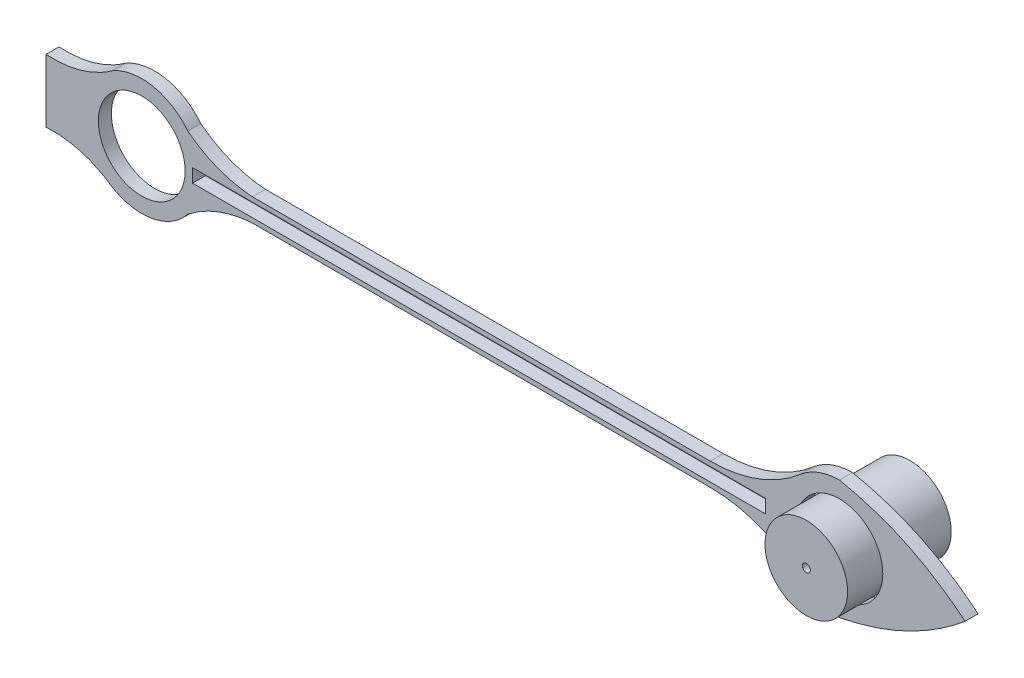
SolidWorks part; units mm, degrees
ref_plane "Plan de face" through (0, 0, 0) normal (0, 0, 1) x (1, 0, 0)
ref_plane "Plan de dessus" through (0, 0, 0) normal (0, 1, 0) x (1, 0, 0)
ref_plane "Plan de droite" through (0, 0, 0) normal (1, 0, 0) x (0, 0, -1)
sketch "Esquisse1" plane through (0, 0, 0) normal (0, 0, 1) x (1, 0, 0)
  line L0 (10.3412, -0.1574) -> (1.5013, -0.1574) construction
  line L1 (10.2021, 0) -> (10.2021, 10.4852) construction
  line L2 (2.2237, 0) -> (9.9473, 0) construction
  line L3 (2.2237, 0) -> (8.5558, 0)
  line L4 (0.6927, -0.1574) -> (1.2927, -0.1574) construction
  line L7 (8.5558, -0.3149) -> (2.2237, -0.3149)
  line L9 (1.2927, -0.1574) -> (-0.6312, -0.1574) construction
  line L10 (1.5013, -0.1574) -> (2.3649, -0.1574) construction
  line L11 (-0.6312, 0.2782) -> (-0.6312, -0.5931)
  circle A0 centre (10.3412, -0.1574) radius 0.6
  circle A1 centre (0.6927, -0.1574) radius 0.6
  arc A2 (1.3308, 0.3392) -> (0.2925, 0.5451) centre (0.6927, -0.1574) ccw
  arc A3 (9.8011, -0.7798) -> (10.3412, -0.9815) centre (10.3412, -0.1574) ccw
  arc A4 (9.8011, -0.7798) -> (8.5558, -0.3149) centre (8.5558, -2.2149) ccw
  arc A5 (9.8011, 0.465) -> (8.5558, 0) centre (8.5558, 1.9) cw
  arc A6 (0.2925, -0.86) -> (1.3308, -0.654) centre (0.6927, -0.1574) ccw
  arc A8 (10.3412, 0.6666) -> (9.8011, 0.465) centre (10.3412, -0.1574) ccw
  spline S0 degree 2 poles (10.3412, 0.6666) (11.33, 0.4718) (12.0778, -0.1574) knots 0 0 0 1 1 1
  spline S1 degree 2 poles (10.3412, -0.9815) (11.33, -0.7867) (12.0778, -0.1574) knots 0 0 0 1 1 1
  spline S2 degree 2 poles (-0.6312, 0.2782) (-0.1204, 0.2492) (0.2925, 0.5451) knots 0 0 0 1 1 1
  spline S3 degree 2 poles (-0.6312, -0.5931) (-0.1204, -0.564) (0.2925, -0.86) knots 0 0 0 1 1 1
  spline S4 degree 2 poles (1.3308, 0.3392) (1.7218, 0.0347) (2.2237, 0) knots 0 0 0 1 1 1
  spline S5 degree 2 poles (1.3308, -0.654) (1.7218, -0.3496) (2.2237, -0.3149) knots 0 0 0 1 1 1
  dimension "D1" = 1.9
extrude "Boss.-Extru.1" add sketch "Esquisse1" along normal blind 0.18
sketch "Esquisse2" plane through (0, 0, 0.18) normal (0, 0, 1) x (1, 0, 0)
  line L2 (1.3955, -0.2505) -> (9.3207, -0.2505)
  line L4 (1.3955, -0.2505) -> (1.3955, -0.0643)
  line L5 (1.3955, -0.0643) -> (9.3207, -0.0643)
  line L6 (9.3207, -0.2505) -> (9.3207, -0.0643)
extrude "Enlèv. mat.-Extru.1" cut sketch "Esquisse2" against normal blind 0.18
sketch "Esquisse3" plane through (0, 0, 0.18) normal (0, 0, 1) x (1, 0, 0)
  circle A0 centre (10.3412, -0.1574) radius 0.5713
  circle A1 centre (10.3412, -0.1574) radius 0.0555
extrude "Boss.-Extru.2" add sketch "Esquisse3" along normal blind 0.458 and the other way blind 0.195 separate body
sketch "Esquisse4" plane through (0, 0, -0.015) normal (0, 0, -1) x (-1, 0, 0)
  circle A0 centre (-10.3412, -0.1574) radius 0.5713
  circle A1 centre (-10.3412, -0.1574) radius 0.0822
extrude "Boss.-Extru.3" add sketch "Esquisse4" along normal blind 0.78
